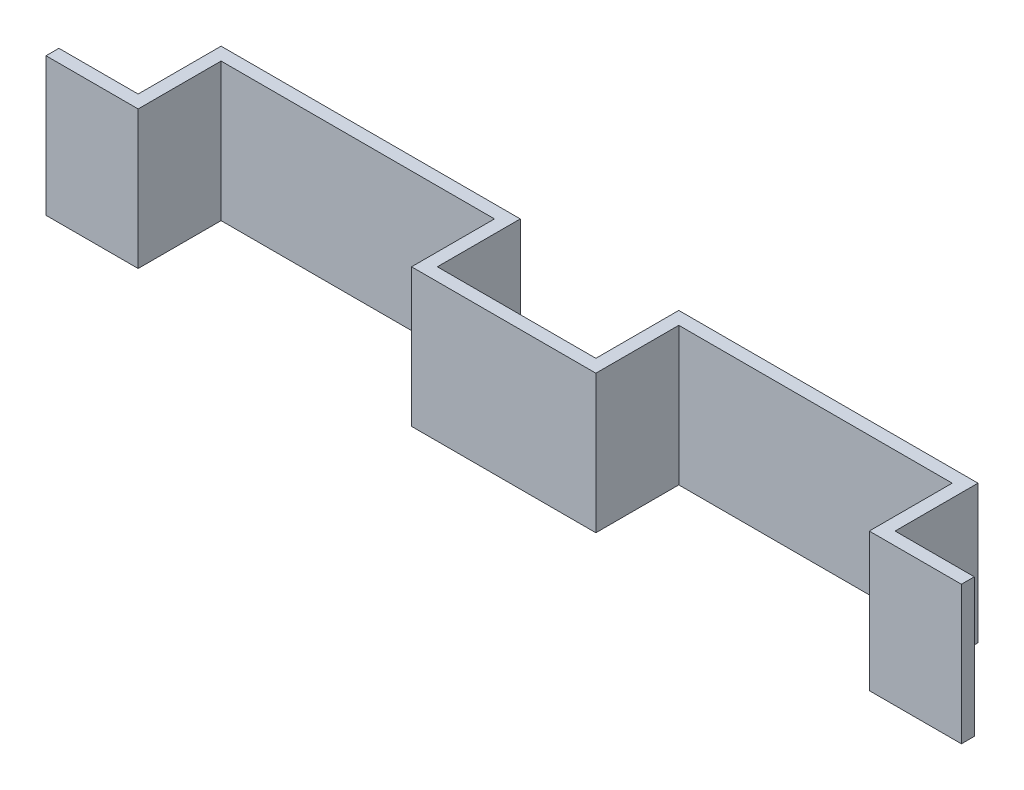
SolidWorks part; units mm, degrees
ref_plane "Front Plane" through (0, 0, 0) normal (1, 0, 0) x (0, 1, 0)
ref_plane "Top Plane" through (0, 0, 0) normal (0, 0, 1) x (0, 1, 0)
ref_plane "Right Plane" through (0, 0, 0) normal (0, 1, 0) x (-1, 0, 0)
sketch "Sketch1" plane through (0, 0, 0) normal (0, 1, 0) x (-1, 0, 0)
  line L0 (0, 0) -> (0, 9)
  line L1 (0, 9) -> (-8.6, 9)
  line L2 (-8.6, 9) -> (-8.6, 10.4)
  line L3 (-8.6, 10.4) -> (1.4, 10.4)
  line L4 (1.4, 10.4) -> (1.4, 1.4)
  line L5 (1.4, 1.4) -> (31.07, 1.4)
  line L6 (31.07, 1.4) -> (31.07, 10.4)
  line L7 (31.07, 10.4) -> (41.07, 10.4)
  line L8 (41.07, 10.4) -> (41.07, 9)
  line L9 (41.07, 9) -> (32.47, 9)
  line L10 (32.47, 9) -> (32.47, 0)
  line L11 (32.47, 0) -> (0, 0)
  line L12 (0, 10.4) -> (0, 9) construction
  line L13 (32.47, 10.4) -> (32.47, 9) construction
  line L14 (32.47, 9) -> (31.07, 9) construction
  line L15 (1.4, 1.4) -> (1.4, 0) construction
  line L16 (0, 9) -> (1.4, 9) construction
  line L17 (41.07, 10.4) -> (51.07, 10.4)
  line L18 (49.67, 9) -> (41.07, 9)
  line L19 (49.67, 0) -> (49.67, 9)
  line L20 (51.07, 10.4) -> (51.07, 1.4)
  line L21 (51.07, 1.4) -> (80.74, 1.4)
  line L22 (82.14, 0) -> (49.67, 0)
  line L23 (80.74, 1.4) -> (80.74, 10.4)
  line L24 (82.14, 9) -> (82.14, 0)
  line L25 (90.74, 9) -> (82.14, 9)
  line L26 (80.74, 10.4) -> (90.74, 10.4)
  line L27 (90.74, 10.4) -> (90.74, 9)
  line L49 (90.74, 10.4) -> (100.74, 10.4) [skipped]
  line L50 (99.34, 9) -> (90.74, 9) [skipped]
  line L51 (99.34, 0) -> (99.34, 9) [skipped]
  line L52 (100.74, 10.4) -> (100.74, 1.4) [skipped]
  line L53 (100.74, 1.4) -> (130.41, 1.4) [skipped]
  line L54 (131.81, 0) -> (99.34, 0) [skipped]
  line L55 (130.41, 1.4) -> (130.41, 10.4) [skipped]
  line L56 (131.81, 9) -> (131.81, 0) [skipped]
  line L57 (140.41, 9) -> (131.81, 9) [skipped]
  line L58 (130.41, 10.4) -> (140.41, 10.4) [skipped]
  line L59 (140.41, 10.4) -> (150.41, 10.4) [skipped]
  line L60 (149.01, 9) -> (140.41, 9) [skipped]
  line L61 (149.01, 0) -> (149.01, 9) [skipped]
  line L62 (150.41, 10.4) -> (150.41, 1.4) [skipped]
  line L63 (150.41, 1.4) -> (180.08, 1.4) [skipped]
  line L64 (181.48, 0) -> (149.01, 0) [skipped]
  line L65 (180.08, 1.4) -> (180.08, 10.4) [skipped]
  line L66 (181.48, 9) -> (181.48, 0) [skipped]
  line L67 (190.08, 9) -> (181.48, 9) [skipped]
  line L68 (180.08, 10.4) -> (190.08, 10.4) [skipped]
  dimension "D1" = 29.67
  dimension "D2" = 1.4
  dimension "D3" = 10
  dimension "D4" = 10
  dimension "D5" = 9
  dimension "D6" = 4
extrude "Boss-Extrude2" add sketch "Sketch1" along normal blind 15
